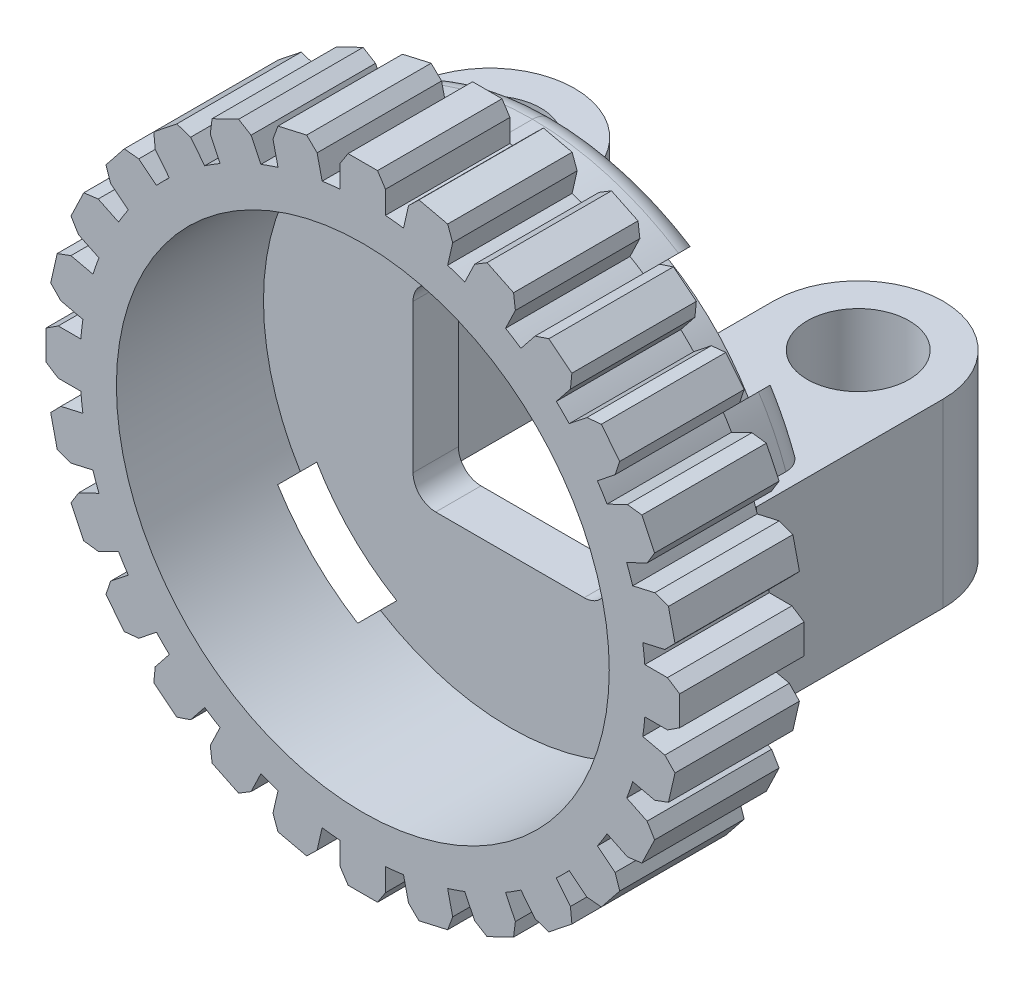
SolidWorks part; units mm, degrees
ref_plane "Front Plane" through (0, 0, 0) normal (0, 0, 1) x (1, 0, 0)
ref_plane "Top Plane" through (0, 0, 0) normal (0, 1, 0) x (1, 0, 0)
ref_plane "Right Plane" through (0, 0, 0) normal (1, 0, 0) x (0, 0, -1)
sketch "Sketch1" plane through (0, 0, 0) normal (0, 0, 1) x (1, 0, 0)
  circle A0 centre (0, 0) radius 12.5
  circle A1 centre (0, 0) radius 10.89
  dimension "D1" = 25
  dimension "D2" = 21.78
extrude "Boss-Extrude2" add sketch "Sketch1" along normal blind 5.5
sketch "Sketch2" plane through (0, 0, 5.5) normal (0, 0, 1) x (1, 0, 0)
  line L0 (0, 0) -> (0, 14) construction
  line L1 (-1, 12.4599) -> (-1, 13.4599)
  line L2 (-1, 13.4599) -> (-0.65, 14)
  line L3 (-0.65, 14) -> (0.65, 14)
  line L4 (1, 12.4599) -> (1, 13.4599)
  line L5 (1, 13.4599) -> (0.65, 14)
  circle A0 centre (0, 0) radius 12.5 construction
  arc A1 (1, 12.4599) -> (-1, 12.4599) centre (0, 0) ccw
  dimension "D1" = 14
  dimension "D2" = 1
  dimension "D3" = 1
  dimension "D4" = 0.65
extrude "Boss-Extrude3" add sketch "Sketch2" against normal blind 5.5
pattern_circular "CirPattern1" count 28 over 360 about axis through (0, 0, 0) along (0, 0, 1) of "Boss-Extrude3"
sketch "Sketch4" plane through (0, 0, 5.5) normal (0, 0, 1) x (1, 0, 0)
  circle A0 centre (0, 0) radius 12.05
  dimension "D1" = 24.1
ref_plane "Plane1" through (0, 0, -3) normal (0, 0, -1) x (-1, 0, 0)
sketch "Sketch9" plane through (0, 0, -3) normal (0, 0, -1) x (-1, 0, 0)
  circle A0 centre (0, 0) radius 9.5
  dimension "D1" = 19
extrude "Boss-Extrude5" add sketch "Sketch9" against normal blind 2 separate body
sketch "Sketch13" plane through (0, 0, 0) normal (0, 0, -1) x (-1, 0, 0)
  line L0 (0, 11.89) -> (0, 0) construction
  circle A0 centre (0, 0) radius 11.89
  circle A1 centre (0, 0) radius 10.89
  point P5 (0, 10.89)
  point P6 (0, 11.89)
  dimension "D1" = 23.78
  dimension "D2" = 21.78
sketch "Sketch15" plane through (0, 0, 0) normal (1, 0, 0) x (0, 0, -1)
  line L0 (0, 11.89) -> (0, 10.89)
  line L1 (0, 10.89) -> (1, 10.89)
  line L2 (1, 10.89) -> (1, 9.5)
  line L3 (1, 9.5) -> (3, 9.5)
  line L4 (3, 9.5) -> (3, 10.89)
  line L5 (2, 11.89) -> (0, 11.89)
  arc A0 (2, 11.89) -> (3, 10.89) centre (2, 10.89) cw
  dimension "D1" = 1
sweep "Sweep2" add profiles "Sketch15" path "Sketch13"
sketch "Sketch16" plane through (0, 0, -3) normal (0, 0, -1) x (-1, 0, 0)
  line L0 (-6.4518, 9.9873) -> (-4.9984, 8.5339)
  line L1 (-9.9873, 6.4518) -> (-8.5339, 4.9984)
  line L2 (0, 0) -> (0, 11.89) construction
  line L3 (9.9873, 6.4518) -> (8.5339, 4.9984)
  line L4 (6.4518, 9.9873) -> (4.9984, 8.5339)
  line L5 (6.4518, -9.9873) -> (4.9984, -8.5339)
  line L6 (9.9873, -6.4518) -> (8.5339, -4.9984)
  line L7 (-9.9873, -6.4518) -> (-8.5339, -4.9984)
  line L8 (-6.4518, -9.9873) -> (-4.9984, -8.5339)
  line L9 (-8.5339, 4.9984) -> (-9.9873, 6.4518)
  line L11 (-4.9984, 8.5339) -> (-6.4518, 9.9873)
  line L13 (4.9984, 8.5339) -> (6.4518, 9.9873)
  line L15 (8.5339, 4.9984) -> (9.9873, 6.4518)
  line L18 (8.5339, -4.9984) -> (9.9873, -6.4518)
  line L19 (4.9984, -8.5339) -> (6.4518, -9.9873)
  line L22 (-4.9984, -8.5339) -> (-6.4518, -9.9873)
  line L24 (-8.5339, -4.9984) -> (-9.9873, -6.4518)
  arc A0 (-4.9984, 8.5339) -> (-8.5339, 4.9984) centre (0, 0) ccw
  circle A1 centre (0, 0) radius 11.89
  arc A2 (-8.5339, -4.9984) -> (-4.9984, -8.5339) centre (0, 0) ccw
  arc A3 (4.9984, -8.5339) -> (8.5339, -4.9984) centre (0, 0) ccw
  arc A4 (8.5339, 4.9984) -> (4.9984, 8.5339) centre (0, 0) ccw
  point P25 (0, 0)
  circle M13 centre (0, 0) radius 10.89
  dimension "D1" = 19.78
  dimension "D2" = 23.78
  dimension "D3" = 5
  dimension "D4" = 2.5
  dimension "D5" = 45
  dimension "D6" = 4
  dimension "D7" = 6.4518
  dimension "D8" = 4.9984
extrude "Cut-Extrude1" cut sketch "Sketch16" against normal blind 3 contours A0 L0 L1 M13 | L0 A1 L1 M13 | A4 L3 L4 M13 | L3 A1 L4 M13 | L5 A1 L6 M13 | A3 L5 L6 M13 | A2 L7 L8 M13 | L7 A1 L8 M13
sketch "Sketch17" plane through (0, 0, -3) normal (0, 0, -1) x (-1, 0, 0)
  line L1 (-3.28, -4.28) -> (3.28, -4.28)
  line L2 (-4.28, -3.28) -> (-4.28, 3.28)
  line L3 (-3.28, 4.28) -> (3.28, 4.28)
  line L4 (4.28, -3.28) -> (4.28, 3.28)
  line L5 (-4.28, -4.28) -> (4.28, 4.28) construction
  line L6 (-4.28, 4.28) -> (4.28, -4.28) construction
  arc A0 (3.28, 4.28) -> (4.28, 3.28) centre (3.28, 3.28) cw
  arc A1 (3.28, -4.28) -> (4.28, -3.28) centre (3.28, -3.28) ccw
  arc A2 (-3.28, -4.28) -> (-4.28, -3.28) centre (-3.28, -3.28) cw
  arc A3 (-4.28, 3.28) -> (-3.28, 4.28) centre (-3.28, 3.28) cw
  point P0 (0, 0)
  dimension "D2" = 1
  dimension "D1" = 8.56
extrude "Cut-Extrude2" cut sketch "Sketch17" against normal blind 3
sketch "Sketch19" plane through (0, 0, 0) normal (0, 1, 0) x (1, 0, 0)
  line L0 (-8.14, 0) -> (-8.14, 8.25) construction
  line L1 (-11.89, 0) -> (-11.89, 8.25)
  line L2 (-4.39, 0) -> (-4.39, 8.25)
  line L3 (-11.89, 2) -> (-11.89, 0) construction
  line L4 (-11.89, 0) -> (-4.39, 0)
  line L5 (-9.1181, 0) -> (-9.8999, 0) construction
  arc A1 (-4.39, 8.25) -> (-11.89, 8.25) centre (-8.14, 8.25) ccw
  circle A2 centre (-8.14, 8.25) radius 2.25
  dimension "D3" = 3.75
  dimension "D4" = 4.5
  dimension "D1" = 7.5
  dimension "D2" = 8.25
extrude "Boss-Extrude6" add sketch "Sketch19" along normal mid plane 8
mirror "Mirror1" about plane through (0, 0, 0) normal (1, 0, 0) of "Boss-Extrude6"
sketch "Sketch20" plane through (0, 0, -1) normal (0, 0, 1) x (1, 0, 0)
  circle A0 centre (0, 0) radius 10.89
extrude "Cut-Extrude3" cut sketch "Sketch20" along normal blind 8
